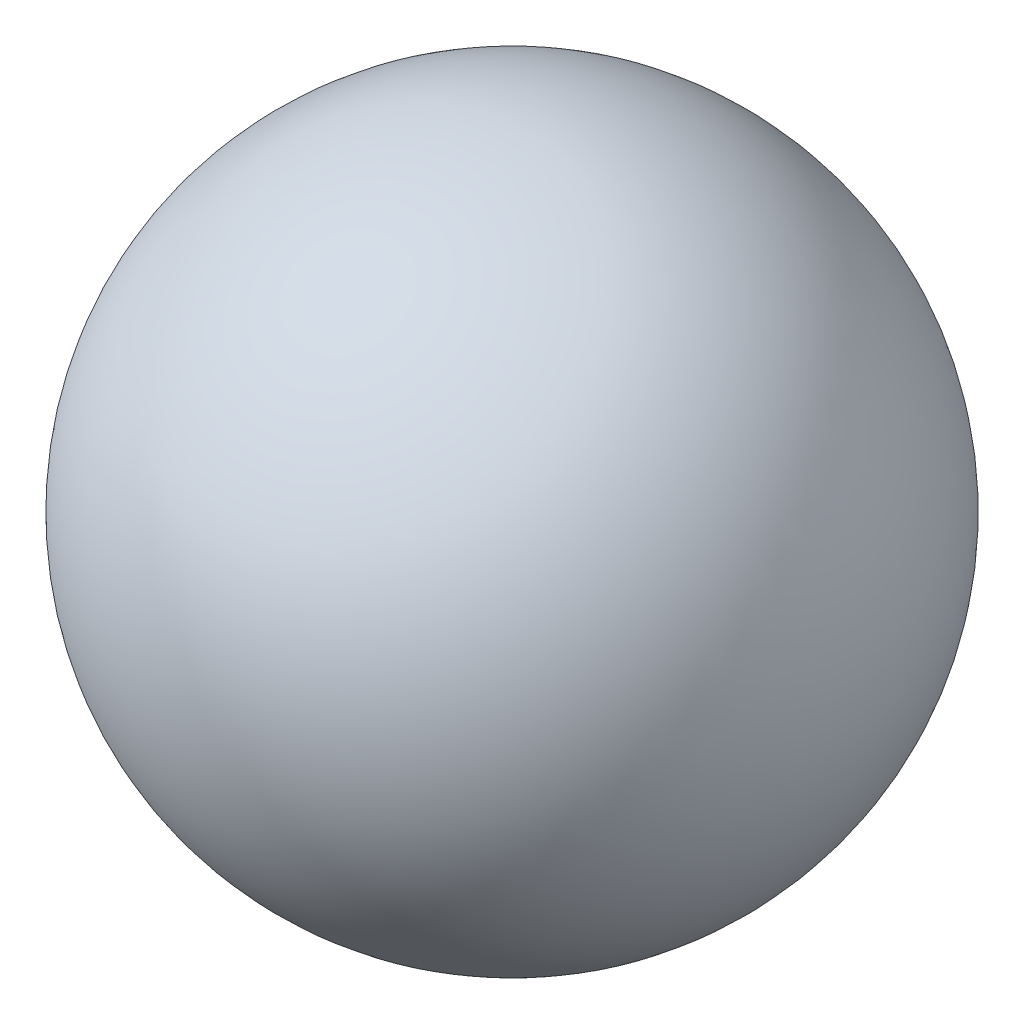
SolidWorks part; units mm, degrees
material "NBR"
ref_plane "前视基准面" through (0, 0, 0) normal (0, 0, 1) x (1, 0, 0)
ref_plane "上视基准面" through (0, 0, 0) normal (0, 1, 0) x (1, 0, 0)
ref_plane "右视基准面" through (0, 0, 0) normal (1, 0, 0) x (0, 0, -1)
sketch "Sketch1" plane through (0, 0, 0) normal (0, 0, 1) x (1, 0, 0)
  line L0 (0, 21.31) -> (0, -21.31)
  arc A0 (0, -21.31) -> (0, 21.31) centre (0, 0) ccw
revolve "Revolve5" add sketch "Sketch1" angle 360 about L0
